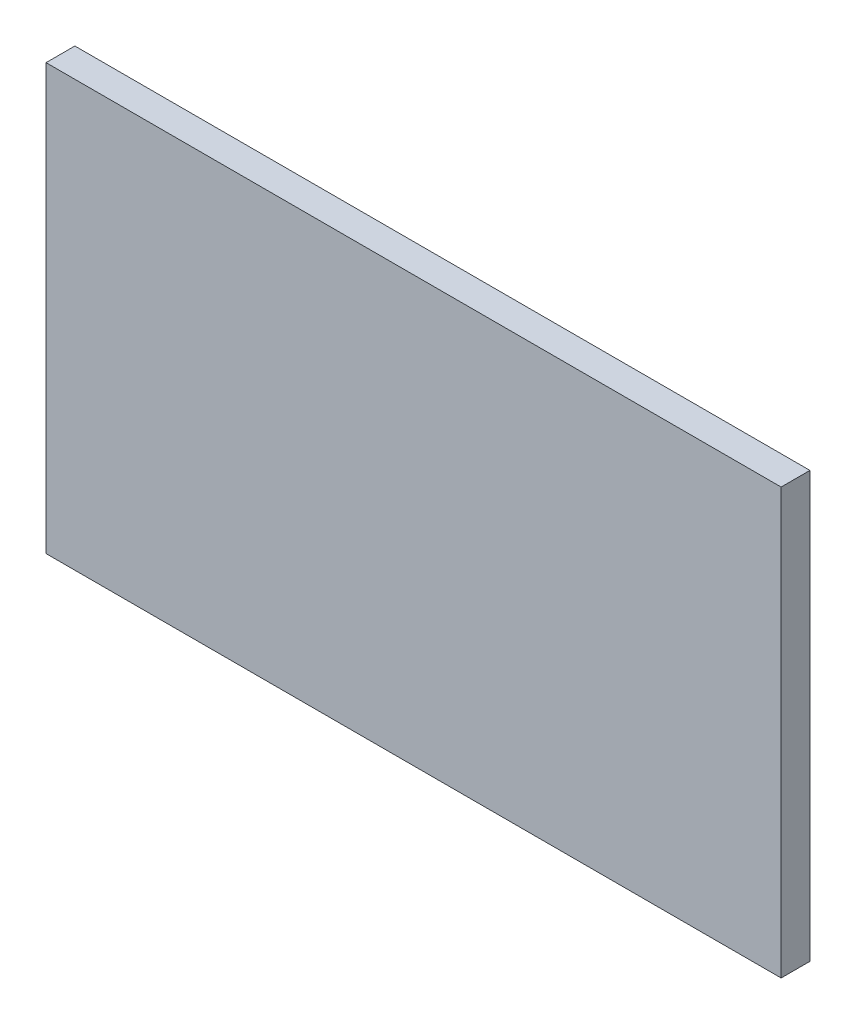
SolidWorks part; units mm, degrees
ref_plane "Alzado" through (0, 0, 0) normal (0, 0, 1) x (1, 0, 0)
ref_plane "Planta" through (0, 0, 0) normal (0, 1, 0) x (1, 0, 0)
ref_plane "Vista lateral" through (0, 0, 0) normal (1, 0, 0) x (0, 0, -1)
sketch "Croquis1" plane through (0, 0, 0) normal (0, 0, 1) x (1, 0, 0)
  line L1 (0, 0) -> (1020, 0)
  line L2 (0, 0) -> (0, 590)
  line L3 (0, 590) -> (1020, 590)
  line L4 (1020, 0) -> (1020, 590)
  point P5 (0, 590)
  dimension "D1" = 590
  dimension "D2" = 1020
extrude "Saliente-Extruir1" add sketch "Croquis1" along normal blind 40
sketch "Croquis2" plane through (0, 0, 0) normal (0, 0, -1) x (-1, 0, 0)
  line L0 (0, 590) -> (0, 0) construction
  line L1 (0, 0) -> (-1020, 0) construction
  line L2 (-1020, 590) -> (0, 590) construction
  line L3 (-1020, 0) -> (-1020, 590) construction
  circle A0 centre (-70, 22.5) radius 7
  circle A1 centre (-70, 567.5) radius 7
  circle A2 centre (-950, 567.5) radius 7
  circle A3 centre (-950, 22.5) radius 7
  dimension "D1" = 70
  dimension "D3" = 22.5
  dimension "D7" = 70
  dimension "D2" = 22.5
  dimension "D4" = 70
  dimension "D5" = 70
  dimension "D6" = 22.5
  dimension "D8" = 22.5
extrude "Cortar-Extruir1" cut sketch "Croquis2" against normal blind 20
